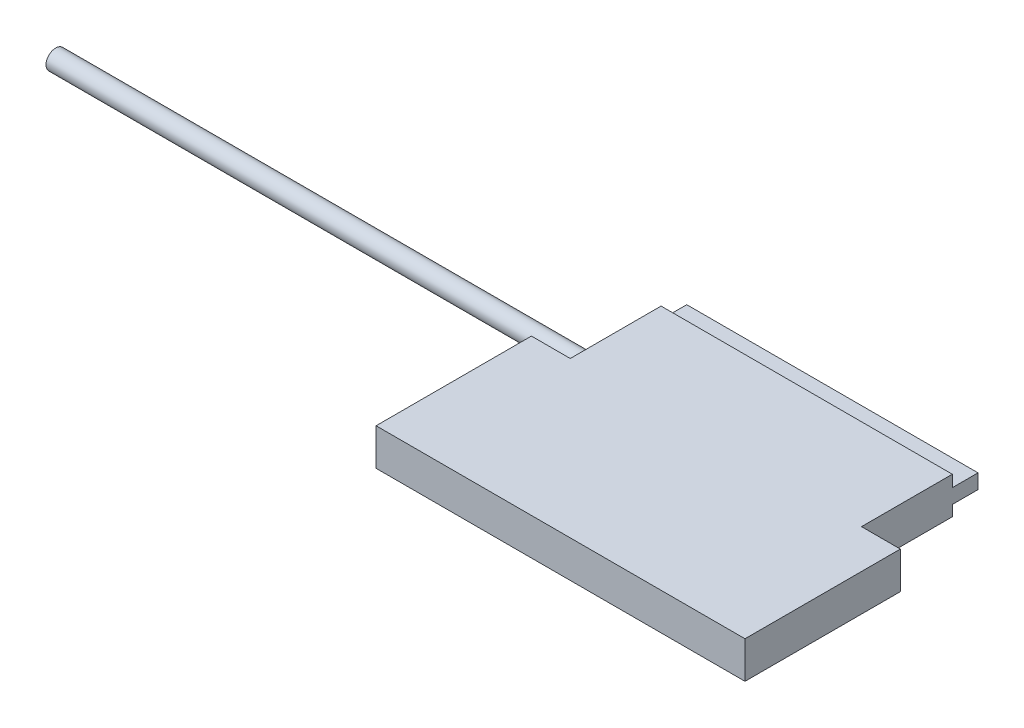
SolidWorks part; units mm, degrees
ref_plane "Ebene vorne" through (0, 0, 0) normal (0, 0, 1) x (1, 0, 0)
ref_plane "Ebene oben" through (0, 0, 0) normal (0, 1, 0) x (1, 0, 0)
ref_plane "Ebene rechts" through (0, 0, 0) normal (1, 0, 0) x (0, 0, -1)
sketch "Skizze1" plane through (0, 0, 0) normal (0, 1, 0) x (1, 0, 0)
  line L0 (0, 0) -> (19, 0)
  line L1 (19, 0) -> (19, 8)
  line L2 (19, 8) -> (17, 8)
  line L3 (17, 8) -> (17, 14)
  line L4 (17, 14) -> (2, 14)
  line L5 (2, 14) -> (2, 8)
  line L6 (2, 8) -> (0, 8)
  line L7 (0, 8) -> (0, 0)
  dimension "D1" = 8
  dimension "D2" = 6
  dimension "D3" = 15
  dimension "D4" = 19
  dimension "D5" = 2
  dimension "D6" = 8
extrude "Aufsatz-Linear austragen1" add sketch "Skizze1" along normal blind 1.9
sketch "Skizze4" plane through (2, 0, 0) normal (-1, 0, 0) x (0, 0, 1)
  line L0 (-14, 1.9) -> (-14, 0) construction
  line L2 (-14, 0) -> (-8, 0) construction
  circle A0 centre (-9.5, 0.5) radius 0.5
  dimension "D1" = 1
  dimension "D2" = 4.5
  dimension "D3" = 0.5
extrude "Aufsatz-Linear austragen3" add sketch "Skizze4" along normal blind 28
sketch "Skizze5" plane through (17, 0, 0) normal (1, 0, 0) x (0, 0, -1)
  line L0 (8, 1.9) -> (14, 1.9) construction
  line L1 (14, 1.9) -> (14, 0) construction
  line L2 (12.6773, 1.9) -> (14, 1.9)
  line L3 (12.6773, 1.9) -> (12.6773, 1.3)
  line L4 (12.6773, 1.3) -> (14, 1.3)
  line L5 (14, 1.9) -> (14, 1.3)
  line L6 (8, 0) -> (14, 0) construction
  line L7 (12.6773, 0) -> (14, 0)
  line L8 (12.6773, 0) -> (12.6773, 0.55)
  line L9 (12.6773, 0.55) -> (14, 0.55)
  line L10 (14, 0) -> (14, 0.55)
  dimension "D1" = 0.75
  dimension "D2" = 0.55
extrude "Schnitt-Linear austragen1" cut sketch "Skizze5" against normal blind 16
